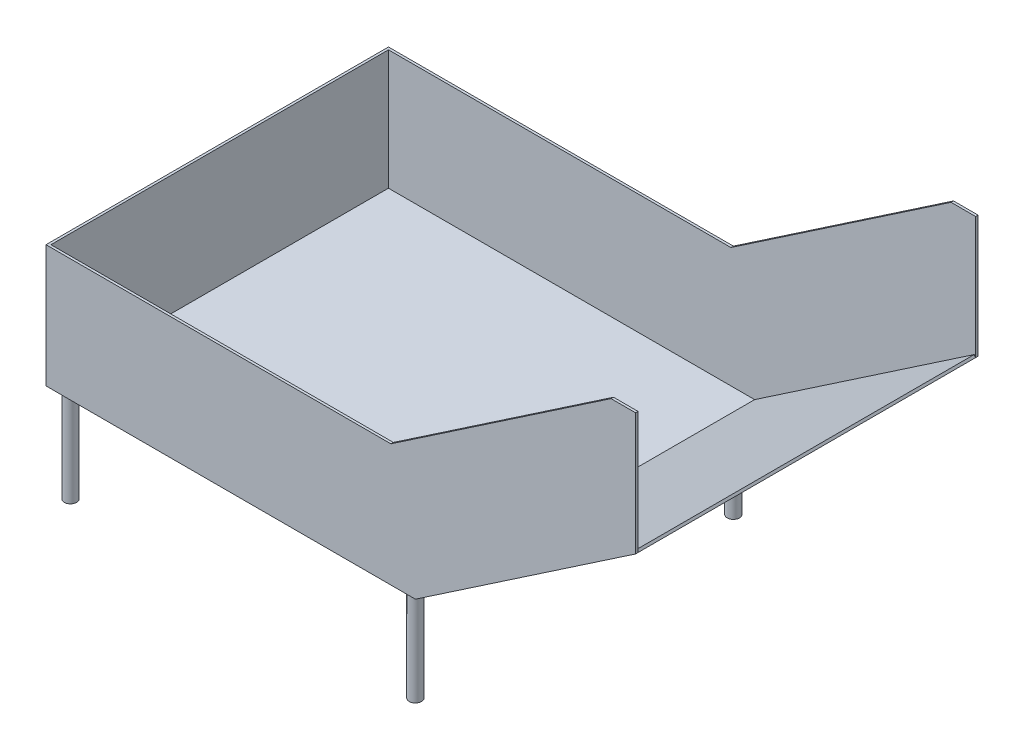
SolidWorks part; units mm, degrees
ref_plane "Front Plane" through (0, 0, 0) normal (0, 0, 1) x (1, 0, 0)
ref_plane "Top Plane" through (0, 0, 0) normal (0, 1, 0) x (1, 0, 0)
ref_plane "Right Plane" through (0, 0, 0) normal (1, 0, 0) x (0, 0, -1)
sketch "Sketch1" plane through (0, 0, 0) normal (0, 0, 1) x (1, 0, 0)
  line L0 (0, 0) -> (0, 50)
  line L1 (0, 50) -> (140, 50)
  line L2 (140, 50) -> (230, 111)
  line L3 (230, 111) -> (240, 111)
  line L4 (240, 111) -> (240, 61)
  line L5 (240, 61) -> (150, 0)
  line L6 (150, 0) -> (0, 0)
  dimension "D1" = 50
  dimension "D2" = 50
  dimension "D3" = 150
  dimension "D4" = 10
  dimension "D5" = 61
  dimension "D6" = 90
extrude "Boss-Extrude1" add sketch "Sketch1" along normal blind 1
sketch "Sketch2" plane through (0, 0, 0) normal (-1, 0, 0) x (0, 0, 1)
  line L1 (1, 0) -> (-139, 0)
  line L2 (1, 0) -> (1, 50)
  line L3 (1, 50) -> (-139, 50)
  line L4 (-139, 0) -> (-139, 50)
  line L5 (1, 50) -> (1, 0) construction
  dimension "D1" = 140
extrude "Boss-Extrude2" add sketch "Sketch2" along normal blind 1
ref_plane "Plane1" through (0, 0, -69) normal (0, 0, 1) x (1, 0, 0)
mirror "Mirror1" about plane through (0, 0, -69) normal (0, 0, 1) of "Boss-Extrude1"
sketch "Sketch3" plane through (0, 0, 0) normal (0, -1, 0) x (1, 0, 0)
  line L1 (-1, 1) -> (150, 1)
  line L2 (-1, 1) -> (-1, -139)
  line L3 (-1, -139) -> (150, -139)
  line L4 (150, 1) -> (150, -139)
extrude "Boss-Extrude3" add sketch "Sketch3" against normal blind 1
ref_plane "Plane2" through (47.2168, -69.6642, 0) normal (0.5611, -0.8278, 0) x (-0.8278, -0.5611, 0)
sketch "Sketch5" plane through (47.2168, -69.6642, 0) normal (0.5611, -0.8278, 0) x (-0.8278, -0.5611, 0)
  line L1 (-232.8916, 139) -> (-124.1671, 139)
  line L2 (-232.8916, 139) -> (-232.8916, -1)
  line L3 (-232.8916, -1) -> (-124.1671, -1)
  line L4 (-124.1671, 139) -> (-124.1671, -1)
extrude "Boss-Extrude4" add sketch "Sketch5" against normal blind 1
sketch "Sketch6" plane through (0, 0, 0) normal (0, -1, 0) x (1, 0, 0)
  line L0 (-1, -139) -> (-1, 1) construction
  line L1 (-1, 1) -> (150, 1) construction
  line L2 (-1, -139) -> (150, -139) construction
  line L3 (150, 1) -> (150, -139) construction
  circle A0 centre (4, -4) radius 2.5
  circle A1 centre (4, -134) radius 2.5
  circle A2 centre (145, -4) radius 2.5
  circle A3 centre (145, -134) radius 2.5
  dimension "D1" = 5
  dimension "D2" = 5
  dimension "D3" = 5
  dimension "D4" = 5
  dimension "D5" = 5
extrude "Boss-Extrude5" add sketch "Sketch6" along normal blind 40
